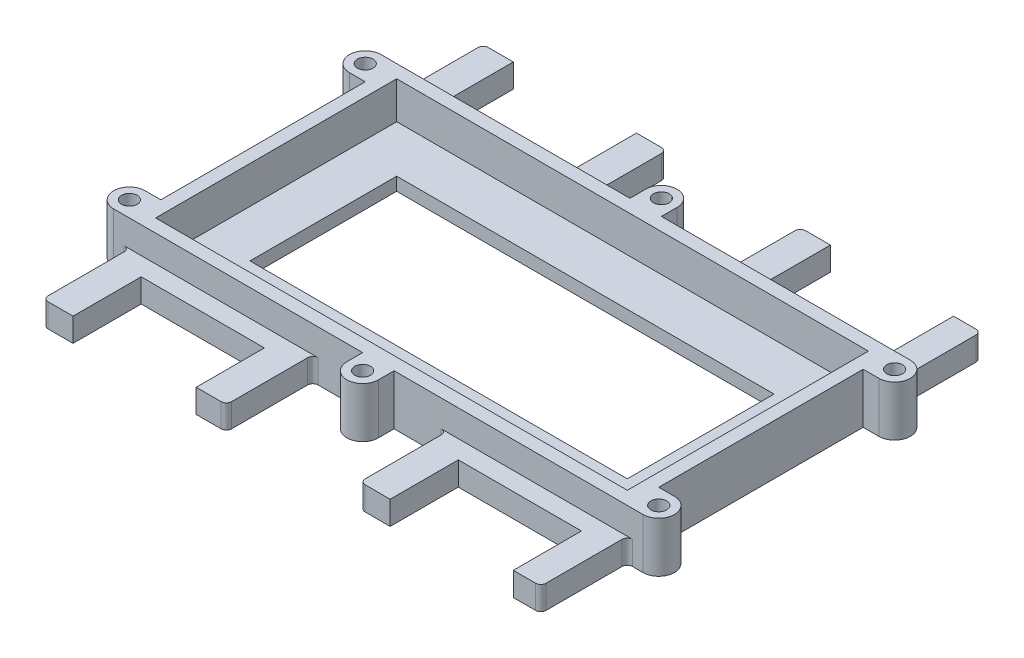
SolidWorks part; units mm, degrees
ref_plane "Front Plane" through (0, 0, 0) normal (0, 0, 1) x (1, 0, 0)
ref_plane "Top Plane" through (0, 0, 0) normal (0, 1, 0) x (1, 0, 0)
ref_plane "Right Plane" through (0, 0, 0) normal (1, 0, 0) x (0, 0, -1)
sketch "Sketch1" plane through (0, 0, 0) normal (0, 1, 0) x (1, 0, 0)
  line L0 (-14.9742, 40.2577) -> (-9.2242, 40.2577)
  line L1 (-44.2242, 40.2577) -> (-38.4742, 40.2577)
  line L2 (-44.2242, 40.2577) -> (-44.2242, -43.7423)
  line L3 (-44.2242, -43.7423) -> (-38.4742, -43.7423)
  line L4 (50.7758, 40.2577) -> (50.7758, -43.7423)
  line L6 (-38.4742, 40.2577) -> (-38.4742, 27.2577)
  line L7 (-38.4742, 27.2577) -> (-14.9742, 27.2577)
  line L8 (-14.9742, 40.2577) -> (-14.9742, 27.2577)
  line L10 (-9.2242, 40.2577) -> (-9.2242, 23.7577)
  line L11 (-9.2242, 23.7577) -> (16.2758, 23.7577)
  line L12 (16.2758, 40.2577) -> (16.2758, 23.7577)
  line L13 (16.2758, 40.2577) -> (22.0258, 40.2577)
  line L14 (3.5258, 23.7577) -> (3.5258, -43.7423) construction
  line L15 (45.5258, 40.2577) -> (50.7758, 40.2577)
  line L17 (45.5258, 40.2577) -> (45.5258, 27.2577)
  line L18 (45.5258, 27.2577) -> (22.0258, 27.2577)
  line L19 (22.0258, 40.2577) -> (22.0258, 27.2577)
  line L20 (-44.2242, -1.7423) -> (50.7758, -1.7423) construction
  line L21 (22.0258, -43.7423) -> (22.0258, -30.7423)
  line L22 (45.5258, -30.7423) -> (22.0258, -30.7423)
  line L23 (45.5258, -43.7423) -> (45.5258, -30.7423)
  line L24 (45.5258, -43.7423) -> (50.7758, -43.7423)
  line L25 (16.2758, -43.7423) -> (22.0258, -43.7423)
  line L26 (16.2758, -43.7423) -> (16.2758, -27.2423)
  line L27 (-9.2242, -27.2423) -> (16.2758, -27.2423)
  line L28 (-9.2242, -43.7423) -> (-9.2242, -27.2423)
  line L29 (-14.9742, -43.7423) -> (-14.9742, -30.7423)
  line L30 (-38.4742, -30.7423) -> (-14.9742, -30.7423)
  line L31 (-38.4742, -43.7423) -> (-38.4742, -30.7423)
  line L32 (-44.2242, -43.7423) -> (-38.4742, -43.7423)
  line L33 (-14.9742, -43.7423) -> (-9.2242, -43.7423)
  line L34 (-14.9742, -43.7423) -> (-9.2242, -43.7423)
  line L35 (16.2758, -43.7423) -> (22.0258, -43.7423)
  line L36 (45.5258, -43.7423) -> (50.7758, -43.7423)
  dimension "D1" = 84
  dimension "D2" = 95
  dimension "D3" = 5.75
  dimension "D4" = 13
  dimension "D5" = 23.5
  dimension "D6" = 5.75
  dimension "D7" = 25.5
  dimension "D8" = 16.5
  dimension "D9" = 5.75
  dimension "D10" = 23.5
  dimension "D11" = 13
extrude "Boss-Extrude1" add sketch "Sketch1" along normal blind 4.5 contours L29 L33 L28 L27 L26 L25 L21 L22 L23 L24 L4 L15 L17 L18 L19 L13 L12 L11 L10 L0 L8 L7 L6 L1 L2 L3 L31 L30
sketch "Sketch2" plane through (0, 4.5, 0) normal (0, 1, 0) x (1, 0, 0)
  line L0 (-9.2242, 23.7577) -> (16.2758, 23.7577) construction
  line L1 (-32.7242, 12.2577) -> (39.2758, 12.2577)
  line L2 (-32.7242, 12.2577) -> (-32.7242, -15.7423)
  line L3 (-32.7242, -15.7423) -> (39.2758, -15.7423)
  line L4 (39.2758, 12.2577) -> (39.2758, -15.7423)
  line L5 (-9.2242, -27.2423) -> (16.2758, -27.2423) construction
  line L6 (50.7758, 40.2577) -> (50.7758, -43.7423) construction
  line L7 (-44.2242, 40.2577) -> (-44.2242, -43.7423) construction
  dimension "D1" = 11.5
  dimension "D2" = 11.5
  dimension "D3" = 11.5
  dimension "D4" = 11.5
extrude "Cut-Extrude1" cut sketch "Sketch2" against normal blind 4.5
sketch "Sketch3" plane through (0, 4.5, 0) normal (0, 1, 0) x (1, 0, 0)
  line L0 (-44.2242, 40.2577) -> (-44.2242, -43.7423) construction
  line L1 (-44.2242, 23.7577) -> (50.7758, 23.7577)
  line L2 (-44.2242, 23.7577) -> (-44.2242, -27.2423)
  line L3 (-44.2242, -27.2423) -> (50.7758, -27.2423)
  line L4 (50.7758, 23.7577) -> (50.7758, -27.2423)
  line L5 (50.7758, 40.2577) -> (50.7758, -43.7423) construction
  line L7 (-41.7242, 21.2577) -> (48.2758, 21.2577)
  line L8 (-41.7242, 21.2577) -> (-41.7242, -24.7423)
  line L9 (-41.7242, -24.7423) -> (48.2758, -24.7423)
  line L10 (48.2758, 21.2577) -> (48.2758, -24.7423)
  dimension "D1" = 2.5
  dimension "D2" = 2.5
  dimension "D3" = 2.5
  dimension "D4" = 2.5
extrude "Boss-Extrude2" add sketch "Sketch3" along normal blind 5.1
sketch "Sketch4" plane through (0, 4.5, 0) normal (0, 1, 0) x (1, 0, 0)
  line L1 (-41.7242, 21.2577) -> (48.2758, 21.2577)
  line L2 (-41.7242, 21.2577) -> (-41.7242, -24.7423)
  line L3 (-41.7242, -24.7423) -> (48.2758, -24.7423)
  line L4 (48.2758, 21.2577) -> (48.2758, -24.7423)
extrude "Cut-Extrude2" cut sketch "Sketch4" against normal blind 2
sketch "Sketch6" plane through (0, 9.6, 0) normal (0, 1, 0) x (1, 0, 0)
  line L0 (-44.2242, -1.7423) -> (50.7758, -1.7423) construction
  line L1 (-44.2242, 23.7577) -> (-47.2242, 23.7577)
  line L2 (-44.2242, 23.7577) -> (-44.2242, 17.7577)
  line L3 (-44.2242, 17.7577) -> (-47.2242, 17.7577)
  line L5 (-44.2242, 23.7577) -> (-44.2242, -27.2423) construction
  line L6 (50.7758, -27.2423) -> (50.7758, 23.7577) construction
  line L7 (3.2758, 23.7577) -> (3.2758, -27.2423) construction
  line L8 (50.7758, 23.7577) -> (-44.2242, 23.7577) construction
  line L9 (-44.2242, -27.2423) -> (50.7758, -27.2423) construction
  line L10 (50.7758, 17.7577) -> (53.7758, 17.7577)
  line L11 (50.7758, 23.7577) -> (50.7758, 17.7577)
  line L12 (50.7758, 23.7577) -> (53.7758, 23.7577)
  line L13 (50.7758, -27.2423) -> (53.7758, -27.2423)
  line L14 (50.7758, -27.2423) -> (50.7758, -21.2423)
  line L15 (50.7758, -21.2423) -> (53.7758, -21.2423)
  line L16 (-44.2242, -21.2423) -> (-47.2242, -21.2423)
  line L17 (-44.2242, -27.2423) -> (-44.2242, -21.2423)
  line L18 (-44.2242, -27.2423) -> (-47.2242, -27.2423)
  line L19 (6.2758, -27.2423) -> (6.2758, -30.2423)
  line L20 (0.2758, 23.7577) -> (6.2758, 23.7577)
  line L21 (0.2758, 23.7577) -> (0.2758, 26.7577)
  line L23 (6.2758, 23.7577) -> (6.2758, 26.7577)
  line L24 (0.2758, -27.2423) -> (0.2758, -30.2423)
  line L25 (0.2758, -27.2423) -> (6.2758, -27.2423)
  arc A0 (-47.2242, 23.7577) -> (-47.2242, 17.7577) centre (-47.2242, 20.7577) ccw
  circle A1 centre (-47.2242, 20.7577) radius 1.5
  circle A2 centre (53.7758, 20.7577) radius 1.5
  arc A3 (53.7758, 23.7577) -> (53.7758, 17.7577) centre (53.7758, 20.7577) cw
  arc A4 (53.7758, -27.2423) -> (53.7758, -21.2423) centre (53.7758, -24.2423) ccw
  circle A5 centre (53.7758, -24.2423) radius 1.5
  circle A6 centre (-47.2242, -24.2423) radius 1.5
  arc A7 (-47.2242, -27.2423) -> (-47.2242, -21.2423) centre (-47.2242, -24.2423) cw
  arc A8 (6.2758, 26.7577) -> (0.2758, 26.7577) centre (3.2758, 26.7577) ccw
  circle A9 centre (3.2758, 26.7577) radius 1.5
  circle A10 centre (3.2758, -30.2423) radius 1.5
  arc A11 (6.2758, -30.2423) -> (0.2758, -30.2423) centre (3.2758, -30.2423) cw
  dimension "D3" = 3
  dimension "D1" = 3
  dimension "D2" = 6
  dimension "D4" = 6
  dimension "D5" = 3
extrude "Boss-Extrude3" add sketch "Sketch6" against normal blind 9.6
fillet "Fillet1" radius 1 16 edges at (-44.2242, 2.25, -23.7577) (50.7758, 2.25, -23.7577) (50.7758, 2.25, 27.2423) (-44.2242, 2.25, 27.2423) (-44.2242, 2.25, 43.7423) (-44.2242, 2.25, -40.2577) (-9.2242, 2.25, -40.2577) (-9.2242, 2.25, -23.7577) (16.2758, 2.25, -23.7577) (16.2758, 2.25, -40.2577) (50.7758, 2.25, -40.2577) (50.7758, 2.25, 43.7423) (16.2758, 2.25, 43.7423) (16.2758, 2.25, 27.2423) (-9.2242, 2.25, 27.2423) (-9.2242, 2.25, 43.7423)
